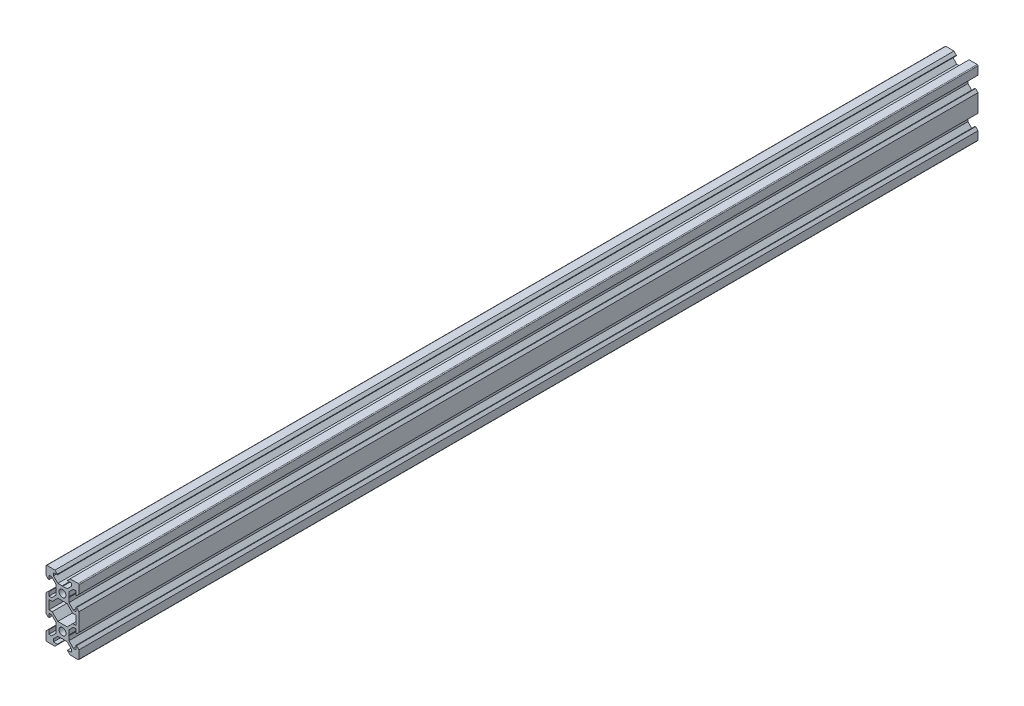
SolidWorks part; units mm, degrees
material "6061-T6 (SS)"
ref_plane "Front Plane" through (0, 0, 0) normal (0, 0, 1) x (1, 0, 0)
ref_plane "Top Plane" through (0, 0, 0) normal (0, 1, 0) x (1, 0, 0)
ref_plane "Right Plane" through (0, 0, 0) normal (1, 0, 0) x (0, 0, -1)
sketch "Sketch1" plane through (0, 0, 0) normal (0, 0, 1) x (1, 0, 0)
  line L0 (0, 0) -> (10, 0) construction
  line L1 (9.5, -20) -> (-9.5, -20)
  line L2 (10, -19.5) -> (10, 19.5)
  line L3 (9.5, 20) -> (-9.5, 20)
  line L4 (-10, -19.5) -> (-10, 19.5)
  line L5 (10, -20) -> (-10, 20) construction
  line L6 (10, 20) -> (-10, -20) construction
  circle A0 centre (0, 10) radius 2.1
  circle A1 centre (0, -10) radius 2.1
  arc A2 (-9.5, -20) -> (-10, -19.5) centre (-9.5, -19.5) cw
  arc A3 (9.5, -20) -> (10, -19.5) centre (9.5, -19.5) ccw
  arc A4 (10, 19.5) -> (9.5, 20) centre (9.5, 19.5) ccw
  arc A5 (-9.5, 20) -> (-10, 19.5) centre (-9.5, 19.5) ccw
  point P0 (0, 0)
  line B0 (0, 10) -> (0, 20) construction
  line B1 (0, 13.69) -> (-0.21, 13.9)
  line B2 (-0.21, 13.9) -> (-2.8393, 13.9)
  line B3 (-2.8393, 13.9) -> (-5.5, 16.5607)
  line B4 (-5.5, 16.5607) -> (-5.5, 18.2)
  line B5 (-5.5, 18.2) -> (-3.125, 18.2)
  line B6 (-3.125, 18.2) -> (-3.125, 18.545)
  line B7 (-3.125, 18.545) -> (-4.58, 20)
  line B8 (-4.58, 20) -> (4.58, 20)
  line B9 (0, 10) -> (-5.9132, 15.9132) construction
  line B10 (3.125, 18.545) -> (4.58, 20)
  line B11 (3.125, 18.2) -> (3.125, 18.545)
  line B12 (5.5, 18.2) -> (3.125, 18.2)
  line B13 (5.5, 16.5607) -> (5.5, 18.2)
  line B14 (2.8393, 13.9) -> (5.5, 16.5607)
  line B15 (0.21, 13.9) -> (2.8393, 13.9)
  line B16 (0, 13.69) -> (0.21, 13.9)
  line B17 (0, 10) -> (-10, 10) construction
  line B18 (-3.69, 10) -> (-3.9, 9.79)
  line B19 (-3.9, 9.79) -> (-3.9, 7.1607)
  line B20 (-3.9, 7.1607) -> (-6.5607, 4.5)
  line B21 (-6.5607, 4.5) -> (-8.2, 4.5)
  line B22 (-8.2, 4.5) -> (-8.2, 6.875)
  line B23 (-8.2, 6.875) -> (-8.545, 6.875)
  line B24 (-8.545, 6.875) -> (-10, 5.42)
  line B25 (-10, 5.42) -> (-10, 14.58)
  line B26 (0, 10) -> (-5.9132, 4.0868) construction
  line B27 (-8.545, 13.125) -> (-10, 14.58)
  line B28 (-8.2, 13.125) -> (-8.545, 13.125)
  line B29 (-8.2, 15.5) -> (-8.2, 13.125)
  line B30 (-6.5607, 15.5) -> (-8.2, 15.5)
  line B31 (-3.9, 12.8393) -> (-6.5607, 15.5)
  line B32 (-3.9, 10.21) -> (-3.9, 12.8393)
  line B33 (-3.69, 10) -> (-3.9, 10.21)
  line B34 (0, -10) -> (-10, -10) construction
  line B35 (-3.69, -10) -> (-3.9, -10.21)
  line B36 (-3.9, -10.21) -> (-3.9, -12.8393)
  line B37 (-3.9, -12.8393) -> (-6.5607, -15.5)
  line B38 (-6.5607, -15.5) -> (-8.2, -15.5)
  line B39 (-8.2, -15.5) -> (-8.2, -13.125)
  line B40 (-8.2, -13.125) -> (-8.545, -13.125)
  line B41 (-8.545, -13.125) -> (-10, -14.58)
  line B42 (-10, -14.58) -> (-10, -5.42)
  line B43 (0, -10) -> (-5.9132, -15.9132) construction
  line B44 (-8.545, -6.875) -> (-10, -5.42)
  line B45 (-8.2, -6.875) -> (-8.545, -6.875)
  line B46 (-8.2, -4.5) -> (-8.2, -6.875)
  line B47 (-6.5607, -4.5) -> (-8.2, -4.5)
  line B48 (-3.9, -7.1607) -> (-6.5607, -4.5)
  line B49 (-3.9, -9.79) -> (-3.9, -7.1607)
  line B50 (-3.69, -10) -> (-3.9, -9.79)
  line B51 (0, -10) -> (0, -20) construction
  line B52 (0, -13.69) -> (0.21, -13.9)
  line B53 (0.21, -13.9) -> (2.8393, -13.9)
  line B54 (2.8393, -13.9) -> (5.5, -16.5607)
  line B55 (5.5, -16.5607) -> (5.5, -18.2)
  line B56 (5.5, -18.2) -> (3.125, -18.2)
  line B57 (3.125, -18.2) -> (3.125, -18.545)
  line B58 (3.125, -18.545) -> (4.58, -20)
  line B59 (4.58, -20) -> (-4.58, -20)
  line B60 (0, -10) -> (5.9132, -15.9132) construction
  line B61 (-3.125, -18.545) -> (-4.58, -20)
  line B62 (-3.125, -18.2) -> (-3.125, -18.545)
  line B63 (-5.5, -18.2) -> (-3.125, -18.2)
  line B64 (-5.5, -16.5607) -> (-5.5, -18.2)
  line B65 (-2.8393, -13.9) -> (-5.5, -16.5607)
  line B66 (-0.21, -13.9) -> (-2.8393, -13.9)
  line B67 (0, -13.69) -> (-0.21, -13.9)
  line B68 (0, -10) -> (10, -10) construction
  line B69 (3.69, -10) -> (3.9, -9.79)
  line B70 (3.9, -9.79) -> (3.9, -7.1607)
  line B71 (3.9, -7.1607) -> (6.5607, -4.5)
  line B72 (6.5607, -4.5) -> (8.2, -4.5)
  line B73 (8.2, -4.5) -> (8.2, -6.875)
  line B74 (8.2, -6.875) -> (8.545, -6.875)
  line B75 (8.545, -6.875) -> (10, -5.42)
  line B76 (10, -5.42) -> (10, -14.58)
  line B77 (0, -10) -> (5.9132, -4.0868) construction
  line B78 (8.545, -13.125) -> (10, -14.58)
  line B79 (8.2, -13.125) -> (8.545, -13.125)
  line B80 (8.2, -15.5) -> (8.2, -13.125)
  line B81 (6.5607, -15.5) -> (8.2, -15.5)
  line B82 (3.9, -12.8393) -> (6.5607, -15.5)
  line B83 (3.9, -10.21) -> (3.9, -12.8393)
  line B84 (3.69, -10) -> (3.9, -10.21)
  line B85 (0, 10) -> (10, 10) construction
  line B86 (3.69, 10) -> (3.9, 10.21)
  line B87 (3.9, 10.21) -> (3.9, 12.8393)
  line B88 (3.9, 12.8393) -> (6.5607, 15.5)
  line B89 (6.5607, 15.5) -> (8.2, 15.5)
  line B90 (8.2, 15.5) -> (8.2, 13.125)
  line B91 (8.2, 13.125) -> (8.545, 13.125)
  line B92 (8.545, 13.125) -> (10, 14.58)
  line B93 (10, 14.58) -> (10, 5.42)
  line B94 (0, 10) -> (5.9132, 15.9132) construction
  line B95 (8.545, 6.875) -> (10, 5.42)
  line B96 (8.2, 6.875) -> (8.545, 6.875)
  line B97 (8.2, 4.5) -> (8.2, 6.875)
  line B98 (6.5607, 4.5) -> (8.2, 4.5)
  line B99 (3.9, 7.1607) -> (6.5607, 4.5)
  line B100 (3.9, 9.79) -> (3.9, 7.1607)
  line B101 (3.69, 10) -> (3.9, 9.79)
  line B102 (-8.2, -2.7) -> (-8.2, 2.7)
  line B103 (-8.2, 2.7) -> (-6.2393, 2.7)
  line B104 (-6.2393, 2.7) -> (-2.8393, 6.1)
  line B105 (-2.8393, 6.1) -> (2.8393, 6.1)
  line B106 (0, 6.1) -> (0, 0) construction
  line B107 (0, 0) -> (-8.2, 0) construction
  line B108 (6.2393, 2.7) -> (2.8393, 6.1)
  line B109 (8.2, 2.7) -> (6.2393, 2.7)
  line B110 (8.2, -2.7) -> (8.2, 2.7)
  line B111 (8.2, -2.7) -> (6.2393, -2.7)
  line B112 (6.2393, -2.7) -> (2.8393, -6.1)
  line B113 (-2.8393, -6.1) -> (2.8393, -6.1)
  line B114 (-6.2393, -2.7) -> (-2.8393, -6.1)
  line B115 (-8.2, -2.7) -> (-6.2393, -2.7)
  line B116 (0, 6.1) -> (0, 10) construction
  line B117 (0, 10) -> (-5.0927, 4.9073) construction
sketch_block_instance "V Slot 1-4"
sketch_block "V Slot 1" parameters "D1"=10, "D2"=11, "D3"=4.3, "D4"=1.8, "D5"=0.21, "D6"=45, "D7"=9.16, "D8"=1.5, "D9"=6.25
sketch_block_instance "V Slot 1-5"
sketch_block_instance "V Slot 1-6"
sketch_block_instance "V Slot 1-7"
sketch_block_instance "V Slot 1-8"
sketch_block_instance "V Slot 1-9"
sketch_block_instance "Center Cutout 1-1"
sketch_block "Center Cutout 1" parameters "D1"=5.4, "D2"=12.2, "D3"=8.2, "D4"=45, "D5"=10, "D6"=1.5
extrude "Boss-Extrude1" add sketch "Sketch1" along normal blind 545 contours B101 B86 B87 B88 B89 B90 B91 B92 L2 A4 L3 B10 B11 B12 B13 B14 B15 B16 B1 B2 B3 B4 B5 B6 B7 A5 L4 B27 B28 B29 B30 B31 B32 B33 B18 B19 B20 B21 B22 B23 B24 B44 B45 B46 B47 B48 B49 B50 B35
equation "\"L\"= 545"
equation "\"D1@Boss-Extrude1\"=\"L\""
